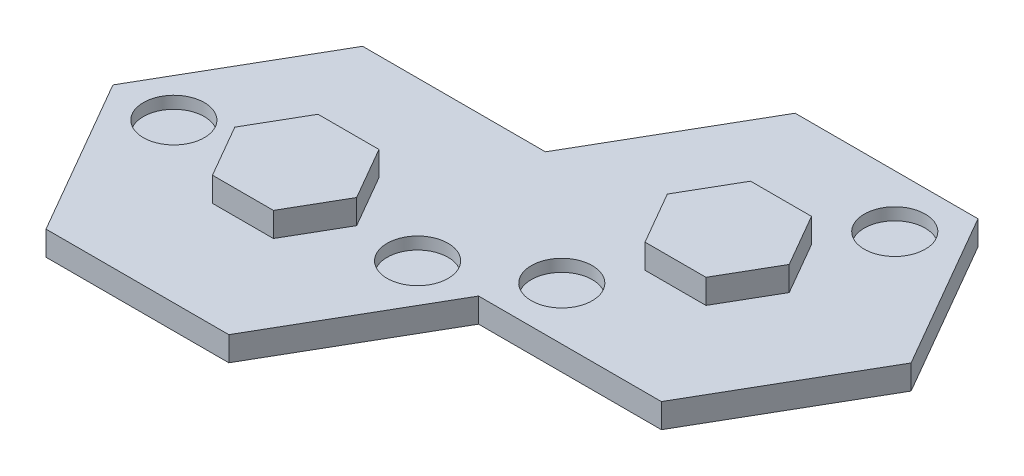
SolidWorks part; units mm, degrees
ref_plane "Front Plane" through (0, 0, 0) normal (0, 0, 1) x (1, 0, 0)
ref_plane "Top Plane" through (0, 0, 0) normal (0, 1, 0) x (1, 0, 0)
ref_plane "Right Plane" through (0, 0, 0) normal (1, 0, 0) x (0, 0, -1)
sketch "Sketch1" plane through (0, 0, 0) normal (0, 1, 0) x (1, 0, 0)
  line L1 (38.1, 65.9911) -> (-38.1, 65.9911)
  line L2 (-38.1, 65.9911) -> (-76.2, 0)
  line L3 (-76.2, 0) -> (-38.1, -65.9911)
  line L4 (-38.1, -65.9911) -> (38.1, -65.9911)
  line L5 (38.1, -65.9911) -> (76.2, 0)
  line L6 (76.2, 0) -> (38.1, 65.9911)
  circle A0 centre (0, 0) radius 65.9911 construction
  point P1 (0, 0)
  point P10 (0, 0)
  dimension "D1" = 76.2
extrude "Boss-Extrude1" add sketch "Sketch1" along normal blind 10.16
sketch "Sketch2" plane through (0, 10.16, 0) normal (0, 1, 0) x (1, 0, 0)
  line L0 (103.601, 0) -> (-90.3189, 0) construction
  line L1 (0, -5.588) -> (0, 5.588) construction
  circle A0 centre (-50.8, 0) radius 12.7
  circle A2 centre (50.8, 0) radius 12.7
  dimension "D1" = 25.4
  dimension "D2" = 50.8
extrude "Cut-Extrude1" cut sketch "Sketch2" against normal blind 5.08
mirror "Mirror1" about plane through (76.2, 10.16, 0) normal (-0.866, 0, 0.5) of "Cut-Extrude1", "Boss-Extrude1"
sketch "Sketch3" plane through (0, 10.16, 0) normal (0, 1, 0) x (1, 0, 0)
  line L1 (12.7, 21.997) -> (-12.7, 21.997)
  line L2 (-12.7, 21.997) -> (-25.4, 0)
  line L3 (-25.4, 0) -> (-12.7, -21.997)
  line L4 (-12.7, -21.997) -> (12.7, -21.997)
  line L5 (12.7, -21.997) -> (25.4, 0)
  line L6 (25.4, 0) -> (12.7, 21.997)
  circle A0 centre (0, 0) radius 21.997 construction
  point P1 (0, 0)
  dimension "D1" = 25.4
extrude "Boss-Extrude2" add sketch "Sketch3" along normal blind 10.16
ref_plane "Plane1" through (57.15, 0, -32.9956) normal (0.866, 0, -0.5) x (-0.5, 0, -0.866)
mirror "Mirror2" about plane through (57.15, 0, -32.9956) normal (0.866, 0, -0.5) of "Boss-Extrude2"
